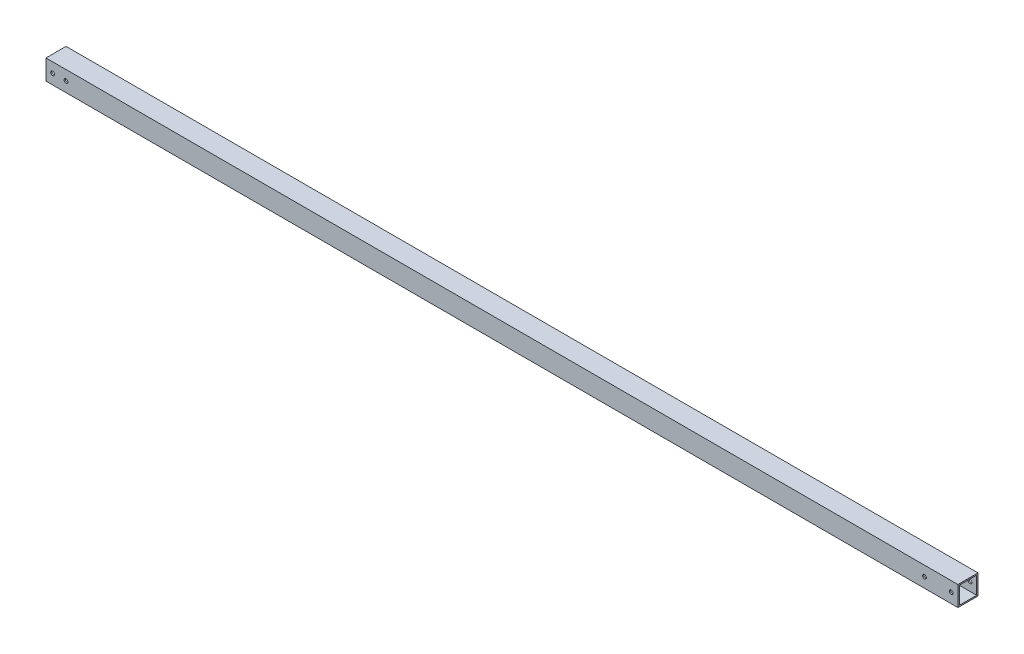
SolidWorks part; units mm, degrees
material "6061 合金"
ref_plane "前视基准面" through (0, 0, 0) normal (0, 0, 1) x (1, 0, 0)
ref_plane "上视基准面" through (0, 0, 0) normal (0, 1, 0) x (1, 0, 0)
ref_plane "右视基准面" through (0, 0, 0) normal (1, 0, 0) x (0, 0, -1)
other "Configuration Table"
sketch "草图1" plane through (0, 0, 0) normal (1, 0, 0) x (0, 0, -1)
  line L0 (-6.5, -6.5) -> (-6.5, 6.5)
  line L1 (-7.5, -7.5) -> (7.5, -7.5)
  line L2 (-7.5, -7.5) -> (-7.5, 7.5)
  line L3 (-7.5, 7.5) -> (7.5, 7.5)
  line L4 (7.5, -7.5) -> (7.5, 7.5)
  line L5 (-7.5, -7.5) -> (7.5, 7.5) construction
  line L6 (-7.5, 7.5) -> (7.5, -7.5) construction
  line L7 (-6.5, 6.5) -> (6.5, 6.5)
  line L8 (6.5, -6.5) -> (6.5, 6.5)
  line L9 (-6.5, -6.5) -> (6.5, -6.5)
  point P0 (0, 0)
  dimension "D1" = 15
  dimension "D2" = 15
  dimension "D3" = 1
extrude "凸台-拉伸1" add sketch "草图1" along normal blind 681.8
sketch "草图2" plane through (0, 0, -7.5) normal (0, 0, -1) x (-1, 0, 0)
  circle A0 centre (-5, 0) radius 1.45 construction
  circle A1 centre (-15, 0) radius 1.45 construction
  circle A2 centre (-5, 0) radius 1.45
  circle A3 centre (-15, 0) radius 1.45
  circle A4 centre (-656.8, 0) radius 1.45 construction
  circle A5 centre (-676.8, 0) radius 1.45 construction
  circle A6 centre (-656.8, 0) radius 1.45
  circle A7 centre (-676.8, 0) radius 1.45
extrude "切除-拉伸1" cut sketch "草图2" against normal through all
